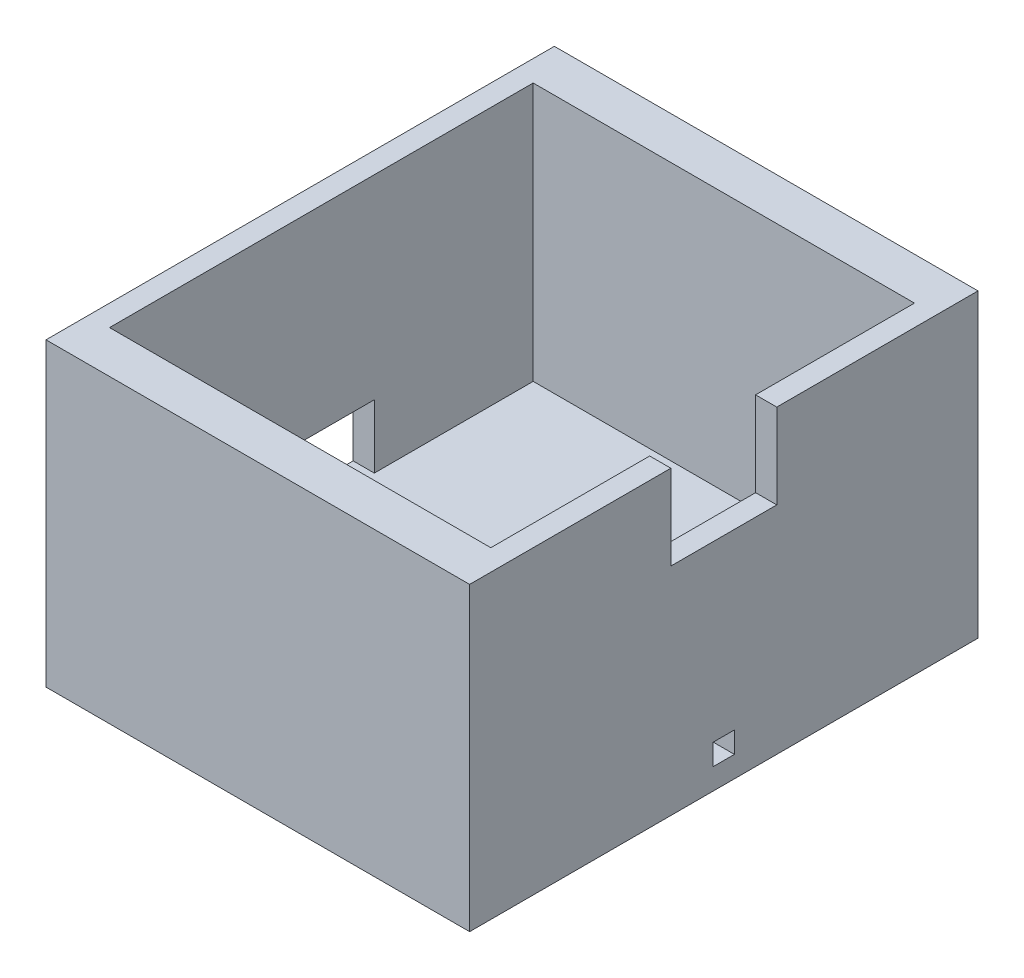
SolidWorks part; units mm, degrees
ref_plane "Front Plane" through (0, 0, 0) normal (0, 0, 1) x (1, 0, 0)
ref_plane "Top Plane" through (0, 0, 0) normal (0, 1, 0) x (1, 0, 0)
ref_plane "Right Plane" through (0, 0, 0) normal (1, 0, 0) x (0, 0, -1)
sketch "Sketch1" plane through (0, 0, 0) normal (0, 1, 0) x (1, 0, 0)
  line L1 (50, -60) -> (-50, -60)
  line L2 (50, -60) -> (50, 60)
  line L3 (50, 60) -> (-50, 60)
  line L4 (-50, -60) -> (-50, 60)
  line L5 (50, -60) -> (-50, 60) construction
  line L6 (50, 60) -> (-50, -60) construction
  point P0 (0, 0)
  dimension "D1" = 100
  dimension "D2" = 120
extrude "Boss-Extrude1" add sketch "Sketch1" along normal blind 10
sketch "Sketch2" plane through (0, 10, 0) normal (0, 1, 0) x (1, 0, 0)
  line L0 (-50, 60) -> (-50, -60) construction
  line L1 (-50, 2.5) -> (50, 2.5)
  line L2 (-50, 2.5) -> (-50, -2.5)
  line L3 (-50, -2.5) -> (50, -2.5)
  line L4 (50, 2.5) -> (50, -2.5)
  line L5 (50, -60) -> (50, 60) construction
  point P8 (-50, 0)
  dimension "D1" = 5
extrude "Cut-Extrude1" cut sketch "Sketch2" against normal blind 5
sketch "Sketch3" plane through (0, 10, 0) normal (0, 1, 0) x (1, 0, 0)
  circle A0 centre (13.1, -18.7267) radius 2
  circle A1 centre (-36.9, -18.7267) radius 2
  dimension "D1" = 4
  dimension "D2" = 4
extrude "Cut-Extrude2" cut sketch "Sketch3" against normal blind 10
sketch "Sketch4" plane through (0, 10, 0) normal (0, 1, 0) x (1, 0, 0)
  line L0 (-50, -60) -> (50, -60) construction
  line L2 (-50, 60) -> (-50, -60)
  line L4 (-45, 50) -> (-45, -50)
  line L6 (50, 60) -> (-50, 60)
  line L7 (50, 60) -> (50, -60)
  line L8 (50, -60) -> (-50, -60)
  line L9 (45, 50) -> (45, -50)
  line L12 (45, -50) -> (-45, -50)
  line L16 (-45, 50) -> (45, 50)
  point P1 (0, 0)
  point P3 (0, 0)
  dimension "D1" = 10
  dimension "D2" = 10
  dimension "D3" = 5
  dimension "D4" = 5
extrude "Boss-Extrude2" add sketch "Sketch4" along normal up to vertex (61 mm away)
sketch "Sketch5" plane through (-50, 0, 0) normal (-1, 0, 0) x (0, 0, 1)
  line L0 (-2.5, 10) -> (2.5, 10) construction
  line L1 (-12.5, 10) -> (12.5, 10)
  line L2 (-12.5, 10) -> (-12.5, 25)
  line L3 (-12.5, 25) -> (12.5, 25)
  line L4 (12.5, 10) -> (12.5, 25)
  point P6 (0, 10)
  dimension "D1" = 15
  dimension "D2" = 25
extrude "Cut-Extrude3" cut sketch "Sketch5" against normal blind 29
sketch "Sketch6" plane through (50, 0, 0) normal (1, 0, 0) x (0, 0, -1)
  line L0 (-60, 71) -> (60, 71) construction
  line L1 (-12.5, 71) -> (12.5, 71)
  line L2 (-12.5, 71) -> (-12.5, 51)
  line L3 (-12.5, 51) -> (12.5, 51)
  line L4 (12.5, 71) -> (12.5, 51)
  line L5 (-10, 52) -> (10, 52) construction
  point P8 (0, 51)
  dimension "D1" = 25
  dimension "D2" = 1
extrude "Cut-Extrude4" cut sketch "Sketch6" against normal blind 29
